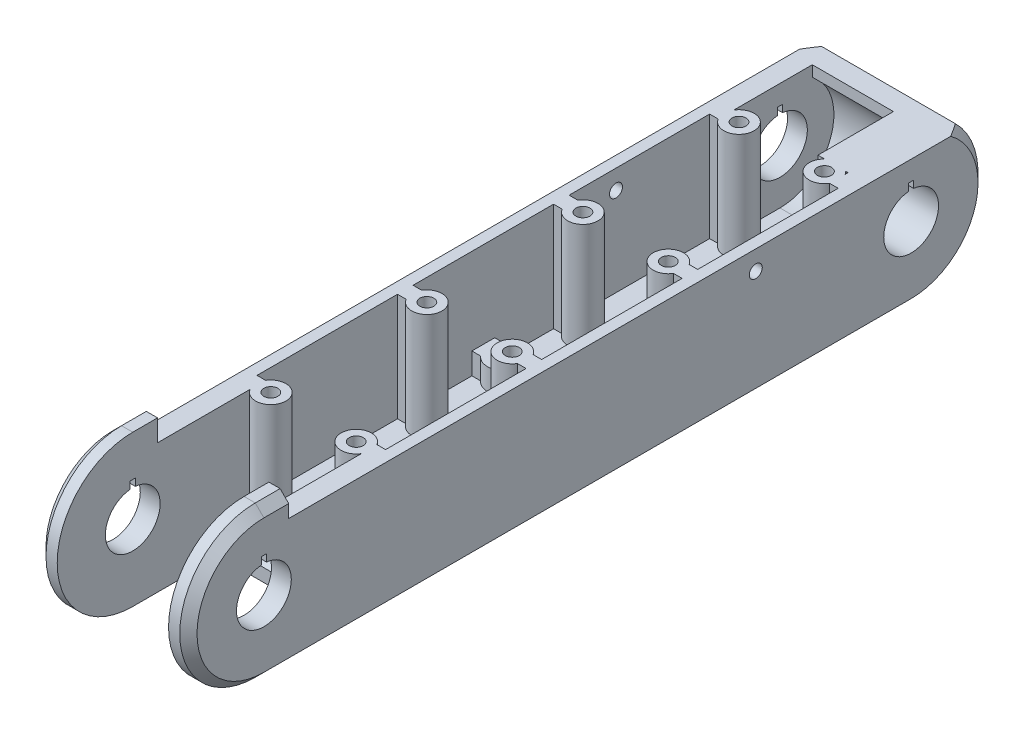
SolidWorks part; units mm, degrees
ref_plane "Front Plane" through (0, 0, 0) normal (0, 0, 1) x (1, 0, 0)
ref_plane "Top Plane" through (0, 0, 0) normal (0, 1, 0) x (1, 0, 0)
ref_plane "Right Plane" through (0, 0, 0) normal (1, 0, 0) x (0, 0, -1)
sketch "Sketch1" plane through (0, 0, 0) normal (1, 0, 0) x (0, 0, -1)
  line L0 (-75, 0) -> (75, 0) construction
  line L2 (-75, -17.5) -> (75, -17.5)
  line L4 (87.2474, 12.5) -> (-69.2474, 12.5)
  line L5 (-75, 17.5) -> (-69.2474, 17.5)
  line L6 (-69.2474, 17.5) -> (-69.2474, 12.5)
  line L7 (-69.2474, 12.5) -> (-87.2474, 12.5) construction
  arc A1 (75, -17.5) -> (87.2474, 12.5) centre (75, 0) ccw
  circle A2 centre (-75, 0) radius 6.35
  circle A3 centre (75, 0) radius 6.35
  arc A4 (-75, 17.5) -> (-75, -17.5) centre (-75, 0) ccw
  point P10 (0, 0)
  dimension "D1" = 17.5
  dimension "D3" = 17.5
  dimension "D5" = 12.7
  dimension "D2" = 150
  dimension "D4" = 5
  dimension "D6" = 18
extrude "Boss-Extrude1" add sketch "Sketch1" along normal mid plane 35
sketch "Sketch3" plane through (0, 0, 0) normal (1, 0, 0) x (0, 0, -1)
  line L0 (-75, 0) -> (75, 0) construction
  line L2 (-55, -12.5) -> (75, -12.5)
  line L3 (-75, -17.5) -> (75, -17.5) construction
  line L9 (-55, -12.5) -> (-55, -17.5)
  line L10 (-55, -17.5) -> (-92.5, -17.5)
  line L11 (-92.5, -17.5) -> (-92.5, 17.5)
  line L13 (82.5, 17.5) -> (82.5, 10)
  line L15 (82.5, 17.5) -> (-92.5, 17.5)
  line L16 (-69.2474, 17.5) -> (-75, 17.5) construction
  circle A2 centre (75, 0) radius 6.35 construction
  arc A3 (-75, 17.5) -> (-75, -17.5) centre (-75, 0) ccw construction
  arc A4 (75, -12.5) -> (82.5, 10) centre (75, 0) ccw
  point P2 (0, 0)
  point P16 (0, 0)
  dimension "D3" = 20
  dimension "D1" = 175
  dimension "D2" = 5
extrude "Cut-Extrude1" cut sketch "Sketch3" against normal mid plane 25.8
chamfer "Chamfer1" distance 2 angle 45 9 edges at (0, -12.5, 55) (-17.5, 0, 92.5) (-17.5, -6.6144, -91.2019) (-17.5, -17.5, 0) (17.5, 0, 92.5) (17.5, -6.6144, -91.2019) (17.5, -17.5, 0) (-17.5, 17.5, 72.1237) (17.5, 17.5, 72.1237)
sketch "Sketch4" plane through (0, -12.5, 0) normal (0, 1, 0) x (1, 0, 0)
  line L0 (-9.9, -46) -> (-9.9, -9.8333) construction
  line L1 (-12.9, -53) -> (-12.9, 75) construction
  line L4 (-12.9, -53) -> (12.9, -53) construction
  line L7 (15.5, 92.5) -> (-15.5, 92.5) construction
  line L8 (-9.9, -9.8333) -> (-9.9, 26.3333) construction
  line L9 (-9.9, 26.3333) -> (-9.9, 62.5) construction
  circle A0 centre (-9.9, 62.5) radius 3.5
  circle A1 centre (-9.9, 26.3333) radius 3.5
  circle A2 centre (-9.9, -9.8333) radius 3.5
  circle A3 centre (-9.9, -46) radius 3.5
  dimension "D1" = 7
  dimension "D2" = 7
  dimension "D3" = 3
  dimension "D4" = 30
extrude "Boss-Extrude2" add sketch "Sketch4" along normal up to surface (25 mm away) up to face at (0.2, 12.5, -23.0835)
sketch "Sketch8" plane through (0, 12.5, 0) normal (0, 1, 0) x (1, 0, 0)
  circle A0 centre (-9.9, 62.5) radius 1.625
  circle A1 centre (-9.9, 26.3333) radius 1.625
  circle A2 centre (-9.9, -9.8333) radius 1.625
  circle A3 centre (-9.9, -46) radius 1.625
  dimension "D1" = 3.25
extrude "Cut-Extrude4" cut sketch "Sketch8" against normal up to surface (30 mm away) up to face at (0, -17.5, 32.5)
sketch "Sketch7" plane through (0, -17.5, 0) normal (0, -1, 0) x (1, 0, 0)
  circle A0 centre (-9.9, 46) radius 2.2
  circle A1 centre (-9.9, 9.8333) radius 2.2
  circle A2 centre (-9.9, -26.3333) radius 2.2
  circle A3 centre (-9.9, -62.5) radius 2.2
  circle A4 centre (-9.9, 46) radius 1.625 construction
  circle A5 centre (-9.9, 9.8333) radius 1.625 construction
  circle A6 centre (-9.9, -26.3333) radius 1.625 construction
  circle A8 centre (-9.9, -62.5) radius 1.625 construction
  dimension "D1" = 4.4
extrude "Cut-Extrude3" cut sketch "Sketch7" against normal blind 4.5
sketch "Sketch9" plane through (0, -12.5, 0) normal (0, 1, 0) x (1, 0, 0)
  line L0 (-9.9, 26.3333) -> (-9.9, -9.8333) construction
  circle A0 centre (-9.9, 8.25) radius 4
  circle A1 centre (-9.9, 8.25) radius 1.625
  point P6 (-9.9, 8.25)
  dimension "D1" = 8
  dimension "D2" = 3.25
extrude "Boss-Extrude3" add sketch "Sketch9" along normal blind 5 and the other way up to surface (5 mm away) other way up to face at (-9.9, -17.5, 43.8)
sketch "Sketch11" plane through (0, -17.5, 0) normal (0, -1, 0) x (1, 0, 0)
  line L0 (-9.9, 9.8333) -> (-9.9, -26.3333) construction
  circle A0 centre (-9.9, -8.25) radius 2.75
  point P6 (-9.9, -8.25)
  dimension "D1" = 5.5
extrude "Cut-Extrude5" cut sketch "Sketch11" against normal blind 3
mirror "Mirror1" about plane through (0, 0, 0) normal (1, 0, 0) of "Cut-Extrude5", "Boss-Extrude3", "Cut-Extrude3", "Boss-Extrude2", "Cut-Extrude4"
sketch "Sketch12" plane through (0, -17.5, 0) normal (0, -1, 0) x (1, 0, 0)
  circle A0 centre (9.9, -8.25) radius 1.625
  dimension "D1" = 3.25
extrude "Cut-Extrude6" cut sketch "Sketch12" against normal through all both and the other way through all
sketch "Sketch15" plane through (0, 12.5, 0) normal (0, 1, 0) x (1, 0, 0)
  line L1 (-12.9, 60.6972) -> (-14.9, 60.6972)
  line L2 (-12.9, 60.6972) -> (-12.9, 28.1361)
  line L3 (-12.9, 28.1361) -> (-14.9, 28.1361)
  line L4 (-14.9, 60.6972) -> (-14.9, 28.1361)
  line L5 (-12.9, 24.5306) -> (-14.9, 24.5306)
  line L6 (-12.9, 24.5306) -> (-12.9, 10.8958)
  line L7 (-12.9, 10.8958) -> (-14.9, 10.8958)
  line L8 (-14.9, 24.5306) -> (-14.9, 10.8958)
  line L9 (-12.9, 5.6042) -> (-14.9, 5.6042)
  line L10 (-12.9, 5.6042) -> (-12.9, -8.0306)
  line L11 (-12.9, -8.0306) -> (-14.9, -8.0306)
  line L12 (-14.9, 5.6042) -> (-14.9, -8.0306)
  line L13 (-12.9, -11.6361) -> (-14.9, -11.6361)
  line L14 (-12.9, -11.6361) -> (-12.9, -44.1972)
  line L15 (-12.9, -44.1972) -> (-14.9, -44.1972)
  line L16 (-14.9, -11.6361) -> (-14.9, -44.1972)
  dimension "D1" = 2
extrude "Cut-Extrude8" cut sketch "Sketch15" against normal up to surface (25 mm away) up to face at (0, -12.5, -8.7083)
sketch "Sketch16" plane through (0, 12.5, 0) normal (0, 1, 0) x (1, 0, 0)
  line L1 (-12.9, 5.6042) -> (-14.9, 5.6042)
  line L2 (-12.9, 5.6042) -> (-12.9, 10.8958)
  line L3 (-12.9, 10.8958) -> (-14.9, 10.8958)
  line L4 (-14.9, 5.6042) -> (-14.9, 10.8958)
extrude "Cut-Extrude9" cut sketch "Sketch16" against normal up to surface (20 mm away) up to face at (-9.4, -7.5, -8.25)
mirror "Mirror2" about plane through (0, 0, 0) normal (1, 0, 0) of "Cut-Extrude9", "Cut-Extrude6", "Cut-Extrude8"
sketch "Sketch17" plane through (17.5, 0, 0) normal (1, 0, 0) x (0, 0, -1)
  line L0 (39, 12.5) -> (39, -15.5) construction
  line L1 (84.1652, 12.5) -> (-69.2474, 12.5) construction
  line L2 (-75, -15.5) -> (75, -15.5) construction
  line L3 (88.2759, 8) -> (-10.2759, 8) construction
  circle A0 centre (39, 8) radius 1.5
  arc A2 (75, -15.5) -> (84.1652, 12.5) centre (75, 0) ccw construction
  circle A3 centre (75, 0) radius 6.35 construction
  point P18 (39, 8)
  dimension "D3" = 3
  dimension "D1" = 36
  dimension "D2" = 8
extrude "Cut-Extrude10" cut sketch "Sketch17" against normal up to surface (35 mm away) up to face at (-17.5, 3.613, 22.4469)
sketch "Sketch18" plane through (-17.5, 0, 0) normal (-1, 0, 0) x (0, 0, 1)
  line L1 (-75.6, 8) -> (-74.4, 8)
  line L2 (-75.6, 8) -> (-75.6, 0)
  line L3 (-75.6, 0) -> (-74.4, 0)
  line L4 (-74.4, 8) -> (-74.4, 0)
  circle A0 centre (-75, 0) radius 6.35 construction
  point P4 (-75, 0)
  dimension "D1" = 1.2
  dimension "D2" = 8
extrude "Cut-Extrude11" cut sketch "Sketch18" against normal up to surface (35 mm away) up to face at (17.5, 8, -40.5)
mirror "Mirror3" about plane through (0, 0, 0) normal (0, 0, 1) of "Cut-Extrude11"
sketch "Sketch19" plane through (12.9, 0, 0) normal (-1, 0, 0) x (0, 0, 1)
  line L0 (-84.1652, 12.5) -> (69.2474, 12.5) construction
  line L1 (-65, -12.5) -> (-85, -12.5)
  line L2 (-65, -12.5) -> (-65, 12.5)
  line L3 (-65, 12.5) -> (-85, 12.5)
  line L4 (-85, -12.5) -> (-85, 12.5)
  line L5 (-74.4, 8) -> (-75.6, 8) construction
  line L6 (-64.3028, -12.5) -> (-75, -12.5) construction
  point P8 (-75, 8)
  point P9 (-75, -12.5)
  dimension "D1" = 20
extrude "Boss-Extrude4" add sketch "Sketch19" along normal blind 7
sketch "Sketch20" plane through (-17.5, 0, 0) normal (-1, 0, 0) x (0, 0, 1)
  line L0 (-75.6, 6.3216) -> (-75.6, 8)
  line L1 (-75.6, 8) -> (-74.4, 8)
  line L2 (-74.4, 8) -> (-74.4, 6.3216)
  line L3 (-74.4, 6.3216) -> (-74.4, 8) construction
  arc A0 (-75.6, 6.3216) -> (-74.4, 6.3216) centre (-75, 0) ccw
extrude "Cut-Extrude12" cut sketch "Sketch20" against normal up to surface (35 mm away) up to face at (17.5, 3.9929, -75)
